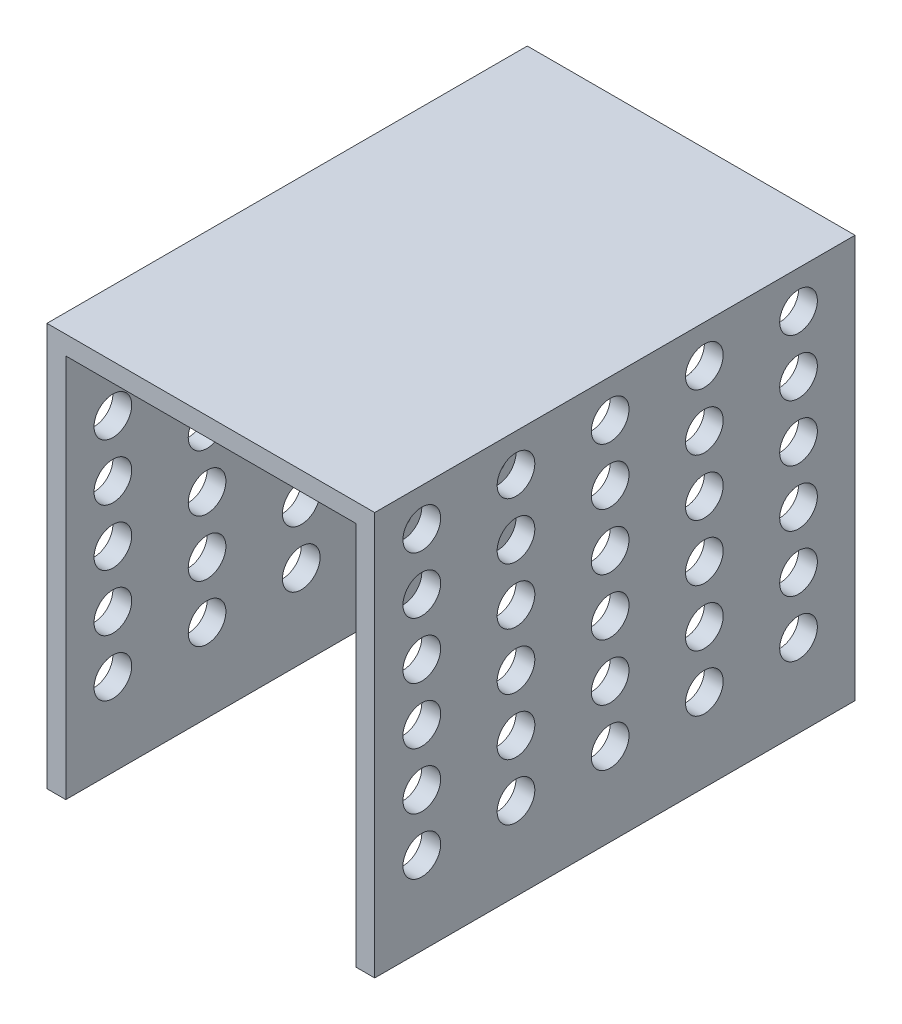
SolidWorks part; units mm, degrees
ref_plane "前视基准面" through (0, 0, 0) normal (0, 0, 1) x (1, 0, 0)
ref_plane "上视基准面" through (0, 0, 0) normal (0, 1, 0) x (1, 0, 0)
ref_plane "右视基准面" through (0, 0, 0) normal (1, 0, 0) x (0, 0, -1)
sketch "草图1" plane through (0, 0, 0) normal (0, 0, 1) x (1, 0, 0)
  line L0 (0, 0) -> (0, -0.5) construction
  line L1 (-8.7, 10.7) -> (8.7, 10.7)
  line L2 (-8.7, 10.7) -> (-8.7, -10.7)
  line L3 (-8.7, -10.7) -> (-7.7, -10.7)
  line L4 (8.7, 10.7) -> (8.7, -10.7)
  line L5 (-8.7, 10.7) -> (8.7, -10.7) construction
  line L6 (-8.7, -10.7) -> (8.7, 10.7) construction
  line L7 (7.7, -10.7) -> (8.7, -10.7)
  line L8 (-7.7, 9.7) -> (7.7, 9.7)
  line L9 (-7.7, 9.7) -> (-7.7, -10.7)
  line L11 (7.7, 9.7) -> (7.7, -10.7)
  line L12 (-7.7, 9.7) -> (7.7, -10.7) construction
  line L13 (-7.7, -10.7) -> (7.7, 9.7) construction
  point P0 (0, 0)
  dimension "D1" = 15.4
  dimension "D2" = 20.4
  dimension "D3" = 1
  dimension "D4" = 1
extrude "凸台-拉伸1" add sketch "草图1" along normal blind 25.5
sketch "草图2" plane through (-8.7, 0, 0) normal (-1, 0, 0) x (0, 0, 1)
  line L0 (3, -10.7) -> (3, 10.7) construction
  line L1 (25.5, -10.7) -> (0, -10.7) construction
  line L2 (25.5, 10.7) -> (0, 10.7) construction
  line L3 (0, 10.7) -> (0, -10.7) construction
  circle A0 centre (3, 8.7) radius 1
  dimension "D1" = 2
  dimension "D2" = 3
  dimension "D3" = 2
extrude "切除-拉伸1" cut sketch "草图2" against normal blind 27
pattern_linear "阵列(线性)1" count 6 spacing 3 along (0, -1, 0) of "切除-拉伸1"
pattern_linear "阵列(线性)2" count 6 spacing 5 along (0, 0, 1) of "阵列(线性)1", "切除-拉伸1"
